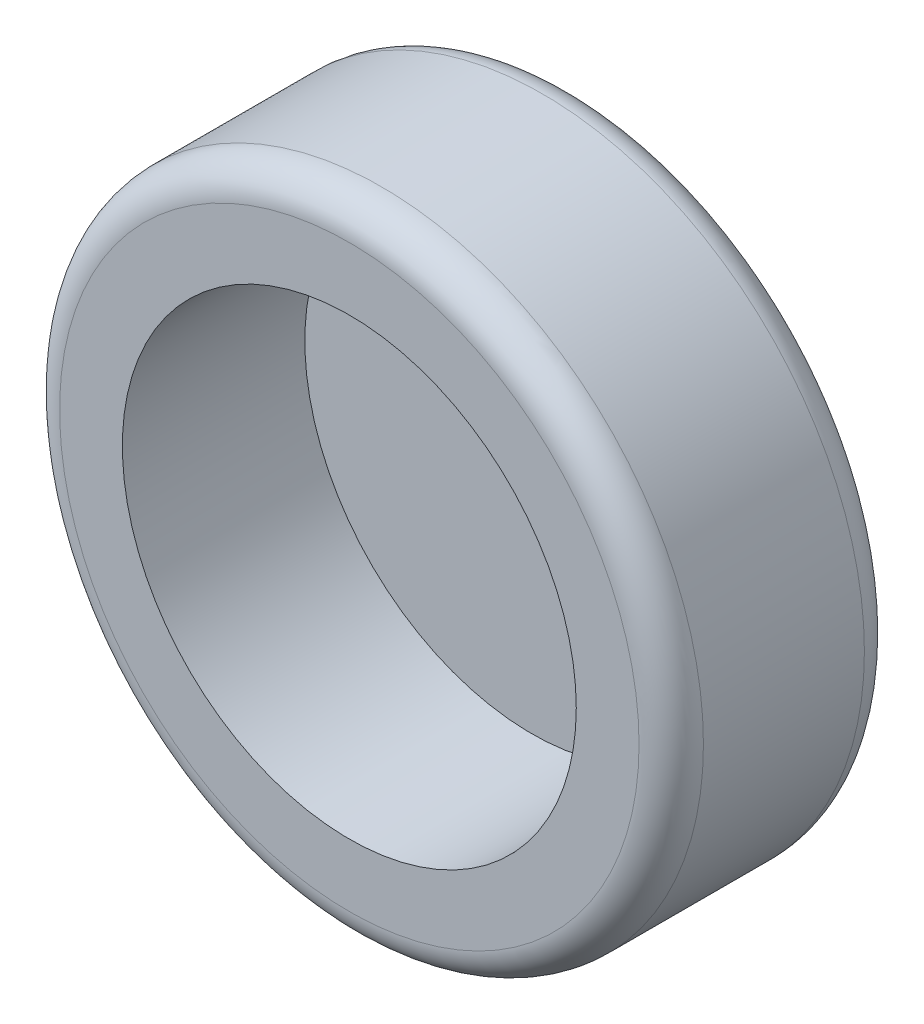
SolidWorks part; units mm, degrees
ref_plane "前视基准面" through (0, 0, 0) normal (0, 0, 1) x (1, 0, 0)
ref_plane "上视基准面" through (0, 0, 0) normal (0, 1, 0) x (1, 0, 0)
ref_plane "右视基准面" through (0, 0, 0) normal (1, 0, 0) x (0, 0, -1)
sketch "草图1" plane through (0, 0, 0) normal (0, 0, 1) x (1, 0, 0)
  circle A0 centre (0, 0) radius 30
  dimension "D1" = 60
extrude "凸台-拉伸1" add sketch "草图1" along normal blind 21
sketch "草图2" plane through (0, 0, 21) normal (0, 0, 1) x (1, 0, 0)
  circle A0 centre (0, 0) radius 21.15
  dimension "D1" = 42.3
extrude "切除-拉伸1" cut sketch "草图2" against normal offset from surface (17 mm away) 4 up to face at (30, 0, 0)
sketch "草图4" plane through (0, 0, 0) normal (0, 1, 0) x (1, 0, 0)
  line L0 (0, 0) -> (0, 50000) construction
  line L1 (30, 0) -> (-30, 0) construction
  line L2 (-25, 0) -> (-27, 0) construction
  line L3 (-30, -3) -> (-30, -18) construction
  line L4 (-30, -21) -> (30, -21) construction
  line L5 (-30, 0) -> (-30, -21) construction
  line L6 (-27, -21) -> (-25, -21)
  line L7 (-25, -21) -> (-25, 0) construction
  line L8 (-27, 0) -> (-30, 0)
  line L9 (-30, 0) -> (-30, -3)
  line L10 (-30, -18) -> (-30, -21)
  line L11 (-30, -21) -> (-27, -21)
  arc A0 (-30, -18) -> (-27, -21) centre (-27, -18) ccw
  arc A1 (-27, 0) -> (-30, -3) centre (-27, -3) ccw
  point P4 (0, 0)
  point P16 (-30, -21)
  point P19 (-30, 0)
  dimension "D2" = 3
  dimension "D1" = 5
revolve "切除-旋转1" cut sketch "草图4" angle 360 about L0
